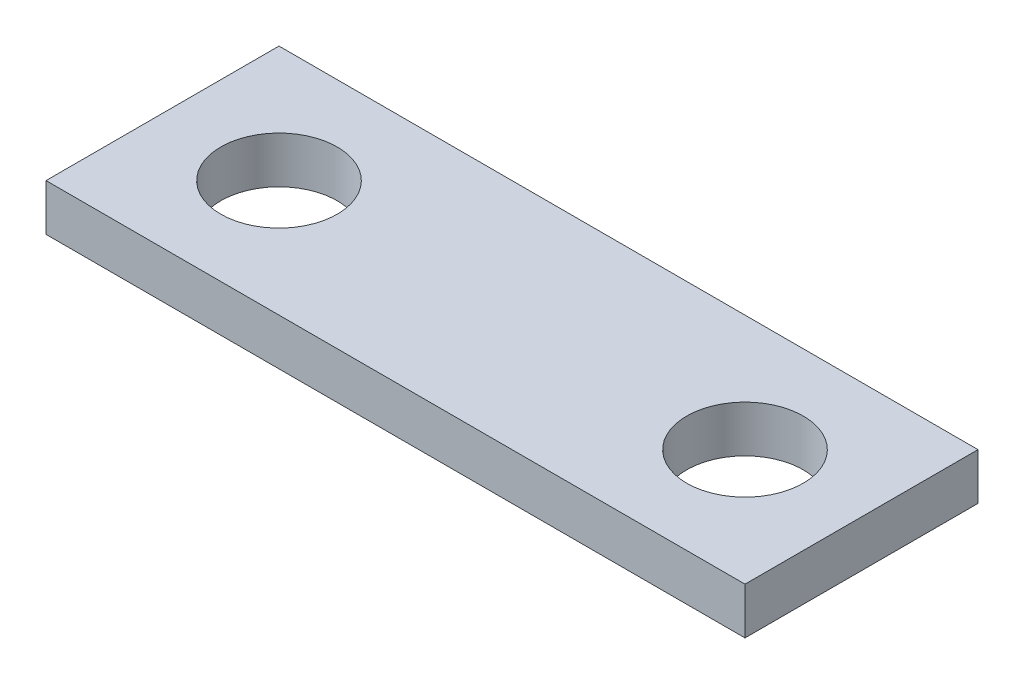
SolidWorks part; units mm, degrees
ref_plane "前视基准面" through (0, 0, 0) normal (0, 0, 1) x (1, 0, 0)
ref_plane "上视基准面" through (0, 0, 0) normal (0, 1, 0) x (1, 0, 0)
ref_plane "右视基准面" through (0, 0, 0) normal (1, 0, 0) x (0, 0, -1)
other "Configuration Table"
sketch "草图1" plane through (0, 0, 0) normal (0, 1, 0) x (1, 0, 0)
  line L1 (-15, -5) -> (15, -5)
  line L2 (-15, -5) -> (-15, 5)
  line L3 (-15, 5) -> (15, 5)
  line L4 (15, -5) -> (15, 5)
  line L5 (-15, -5) -> (15, 5) construction
  line L6 (-15, 5) -> (15, -5) construction
  line L7 (-10, -2.5) -> (10, -2.5)
  line L8 (-10, -2.5) -> (-10, 2.5)
  line L9 (-10, 2.5) -> (10, 2.5)
  line L10 (10, -2.5) -> (10, 2.5)
  line L11 (-10, -2.5) -> (10, 2.5) construction
  line L12 (-10, 2.5) -> (10, -2.5) construction
  circle A0 centre (-10, 0) radius 2.5
  circle A1 centre (10, 0) radius 2.5
  point P0 (0, 0)
  point P6 (0, 0)
  dimension "D5" = 5
  dimension "D1" = 30
  dimension "D2" = 10
  dimension "D3" = 20
  dimension "D4" = 5
extrude "凸台-拉伸1" add sketch "草图1" along normal blind 2 contours L1 L4 L3 L2 A1 L7 A0 L9 | A1 L9 A0 L7
